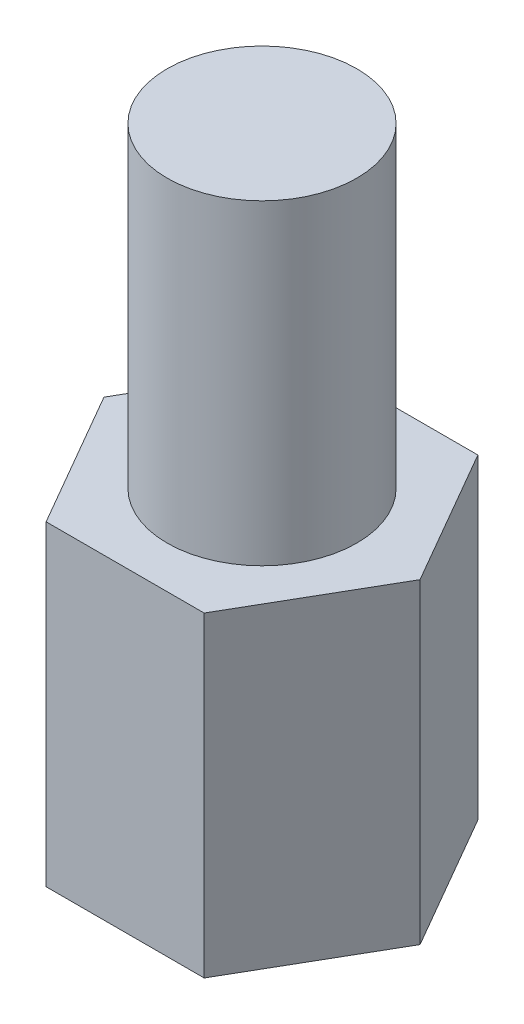
SolidWorks part; units mm, degrees
material "2.0402 (CuZn40Pb2)"
ref_plane "Front" through (0, 0, 0) normal (0, 0, 1) x (1, 0, 0)
ref_plane "Top" through (0, 0, 0) normal (0, 1, 0) x (1, 0, 0)
ref_plane "Right" through (0, 0, 0) normal (1, 0, 0) x (0, 0, -1)
sketch "Эскиз1" plane through (0, 0, 0) normal (0, 1, 0) x (1, 0, 0)
  line L1 (1.25, -2.1651) -> (2.5, 0)
  line L2 (2.5, 0) -> (1.25, 2.1651)
  line L3 (1.25, 2.1651) -> (-1.25, 2.1651)
  line L4 (-1.25, 2.1651) -> (-2.5, 0)
  line L5 (-2.5, 0) -> (-1.25, -2.1651)
  line L6 (-1.25, -2.1651) -> (1.25, -2.1651)
  circle A0 centre (0, 0) radius 2.1651 construction
  circle A1 centre (0, 0) radius 2.5 construction
  dimension "D1" = 5
  dimension "D2" = 2.5
extrude "Бобышка-Вытянуть1" add sketch "Эскиз1" along normal blind 5
sketch "Эскиз2" plane through (0, 5, 0) normal (0, 1, 0) x (1, 0, 0)
  circle A0 centre (0, 0) radius 1.5
  dimension "D1" = 3
extrude "Бобышка-Вытянуть2" add sketch "Эскиз2" along normal blind 5
sketch "Эскиз3" plane through (0, 0, 0) normal (0, -1, 0) x (1, 0, 0)
  circle A0 centre (0, 0) radius 1.5
  dimension "D1" = 3
extrude "Вырез-Вытянуть1" cut sketch "Эскиз3" against normal blind 3
